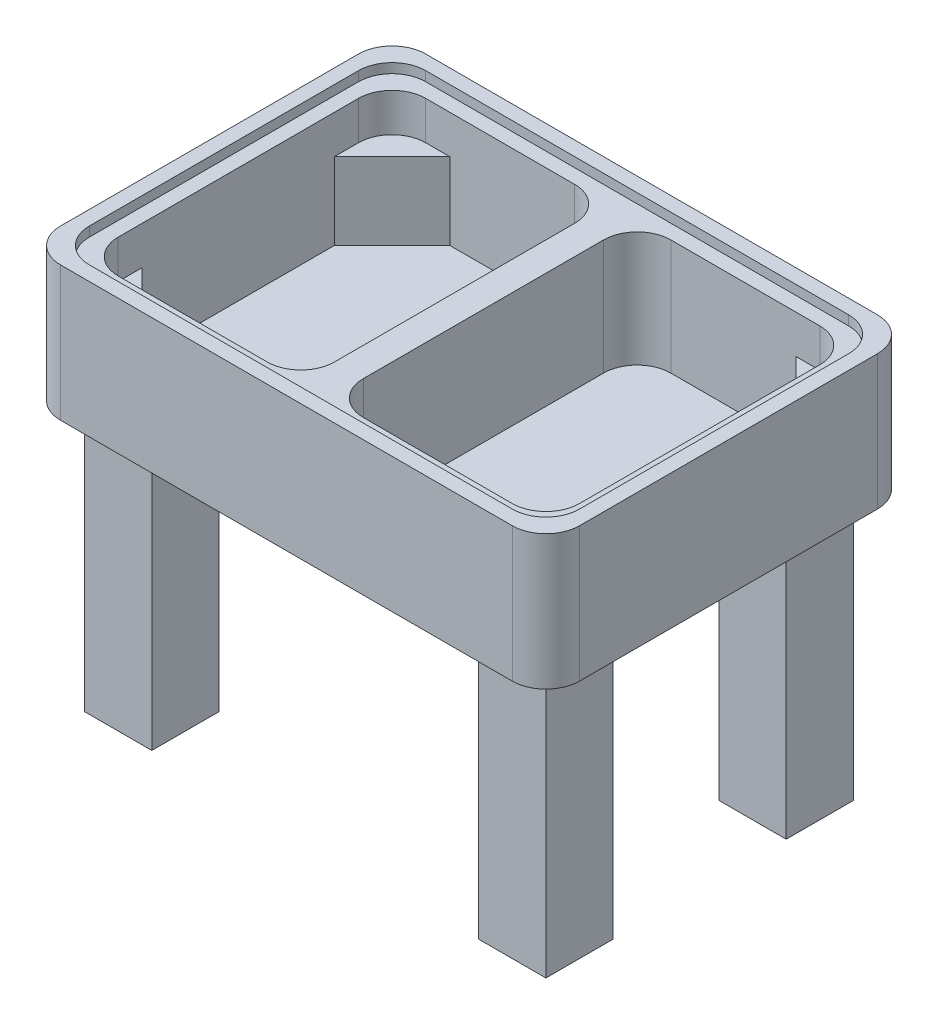
SolidWorks part; units mm, degrees
ref_plane "Front Plane" through (0, 0, 0) normal (0, 0, 1) x (1, 0, 0)
ref_plane "Top Plane" through (0, 0, 0) normal (0, 1, 0) x (1, 0, 0)
ref_plane "Right Plane" through (0, 0, 0) normal (1, 0, 0) x (0, 0, -1)
sketch "Sketch1" plane through (0, 0, 0) normal (0, 1, 0) x (1, 0, 0)
  line L1 (0, 0) -> (540, 0)
  line L2 (0, 0) -> (0, 380)
  line L3 (0, 380) -> (540, 380)
  line L4 (540, 0) -> (540, 380)
  dimension "D1" = 540
  dimension "D2" = 380
extrude "Boss-Extrude1" add sketch "Sketch1" against normal blind 140
sketch "Sketch3" plane through (0, 0, 0) normal (0, 1, 0) x (1, 0, 0)
  line L0 (540, 380) -> (0, 380) construction
  line L1 (15, 365) -> (525, 365)
  line L2 (15, 365) -> (15, 15)
  line L3 (15, 15) -> (525, 15)
  line L4 (525, 365) -> (525, 15)
  line L5 (0, 380) -> (0, 0) construction
  line L6 (0, 0) -> (540, 0) construction
  line L7 (540, 0) -> (540, 380) construction
  dimension "D1" = 15
  dimension "D2" = 15
  dimension "D3" = 15
  dimension "D4" = 15
extrude "Cut-Extrude1" cut sketch "Sketch3" against normal blind 10
sketch "Sketch2" plane through (0, -10, 0) normal (0, 1, 0) x (1, 0, 0)
  line L0 (540, 380) -> (0, 380) construction
  line L1 (30, 350) -> (255, 350)
  line L2 (30, 350) -> (30, 30)
  line L3 (30, 30) -> (255, 30)
  line L4 (255, 350) -> (255, 30)
  line L5 (0, 380) -> (0, 0) construction
  line L6 (0, 0) -> (540, 0) construction
  line L7 (270, 380) -> (270, 0) construction
  line L8 (510, 30) -> (285, 30)
  line L9 (285, 350) -> (285, 30)
  line L10 (510, 350) -> (285, 350)
  line L11 (510, 350) -> (510, 30)
  dimension "D1" = 30
  dimension "D2" = 30
  dimension "D3" = 30
  dimension "D4" = 255
extrude "Cut-Extrude2" cut sketch "Sketch2" against normal blind 40
sketch "Sketch5" plane through (0, -50, 0) normal (0, 1, 0) x (1, 0, 0)
  line L0 (30, 290) -> (90, 350)
  line L1 (30, 350) -> (30, 30) construction
  line L2 (255, 350) -> (30, 350) construction
  line L5 (255, 350) -> (30, 350) construction
  line L6 (255, 350) -> (90, 350)
  line L7 (270, 365) -> (270, 0) construction
  line L8 (525, 365) -> (15, 365) construction
  line L9 (0, 0) -> (540, 0) construction
  line L10 (0, 190) -> (540, 190) construction
  line L11 (0, 380) -> (0, 0) construction
  line L12 (540, 0) -> (540, 380) construction
  line L13 (30, 90) -> (90, 30)
  line L18 (510, 90) -> (450, 30)
  line L21 (510, 290) -> (450, 350)
  line L22 (510, 30) -> (510, 350) construction
  line L23 (285, 30) -> (510, 30) construction
  line L24 (510, 350) -> (285, 350) construction
  line L25 (285, 350) -> (285, 30) construction
  line L26 (255, 30) -> (255, 350) construction
  line L27 (30, 30) -> (255, 30) construction
  line L28 (30, 290) -> (30, 90)
  line L29 (510, 90) -> (510, 290)
  line L30 (285, 30) -> (450, 30)
  line L31 (450, 350) -> (285, 350)
  line L32 (285, 350) -> (285, 30)
  line L33 (255, 30) -> (255, 350)
  line L34 (90, 30) -> (255, 30)
  dimension "D1" = 60
  dimension "D2" = 60
extrude "Cut-Extrude3" cut sketch "Sketch5" against normal blind 80
fillet "Fillet1" radius 35 16 edges at (285, -70, -30) (255, -70, -30) (525, -5, -15) (510, -30, -30) (510, -30, -350) (525, -5, -365) (285, -70, -350) (255, -70, -350) (30, -30, -350) (15, -5, -365) (30, -30, -30) (15, -5, -15) (0, -70, 0) (540, -70, 0) (540, -70, -380) (0, -70, -380)
sketch "Sketch6" plane through (0, -140, 0) normal (0, -1, 0) x (1, 0, 0)
  line L0 (35, 0) -> (505, 0) construction
  line L1 (30, -30) -> (100, -30)
  line L2 (30, -30) -> (30, -100)
  line L3 (30, -100) -> (100, -100)
  line L4 (100, -30) -> (100, -100)
  line L5 (0, -345) -> (0, -35) construction
  line L6 (270, 0) -> (270, -380) construction
  line L7 (505, -380) -> (35, -380) construction
  line L8 (0, -190) -> (540, -190) construction
  line L9 (540, -35) -> (540, -345) construction
  line L10 (510, -100) -> (440, -100)
  line L11 (440, -30) -> (440, -100)
  line L12 (510, -30) -> (440, -30)
  line L13 (510, -30) -> (510, -100)
  line L14 (510, -280) -> (440, -280)
  line L15 (510, -350) -> (510, -280)
  line L16 (510, -350) -> (440, -350)
  line L17 (440, -350) -> (440, -280)
  line L18 (30, -280) -> (100, -280)
  line L19 (100, -350) -> (100, -280)
  line L20 (30, -350) -> (100, -350)
  line L21 (30, -350) -> (30, -280)
  dimension "D1" = 30
  dimension "D2" = 30
  dimension "D3" = 70
  dimension "D4" = 70
extrude "Boss-Extrude2" add sketch "Sketch6" along normal blind 280
